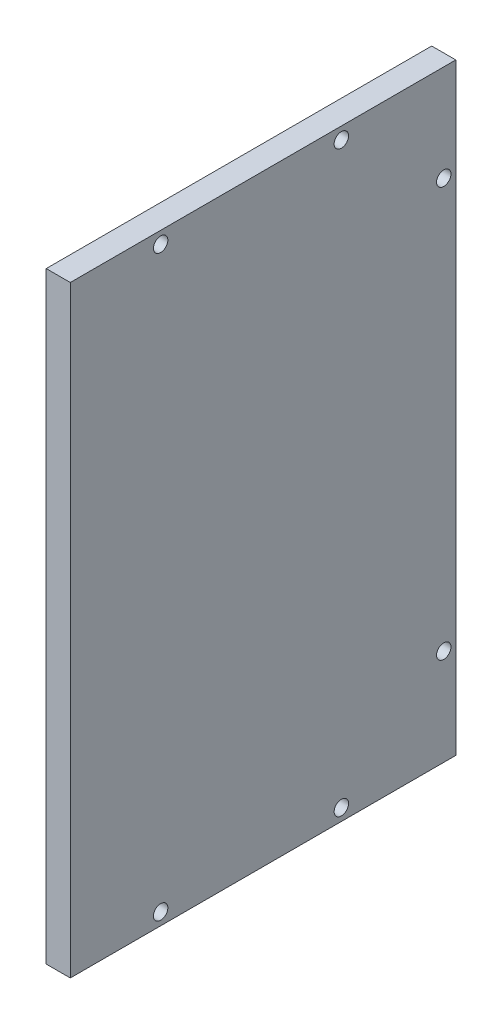
SolidWorks part; units mm, degrees
ref_plane "Front Plane" through (0, 0, 0) normal (0, 0, 1) x (1, 0, 0)
ref_plane "Top Plane" through (0, 0, 0) normal (0, 1, 0) x (1, 0, 0)
ref_plane "Right Plane" through (0, 0, 0) normal (1, 0, 0) x (0, 0, -1)
sketch "Sketch1" plane through (0, 0, 0) normal (1, 0, 0) x (0, 0, -1)
  line L1 (-50.8, -79.375) -> (50.8, -79.375)
  line L2 (-50.8, -79.375) -> (-50.8, 79.375)
  line L3 (-50.8, 79.375) -> (50.8, 79.375)
  line L4 (50.8, -79.375) -> (50.8, 79.375)
  line L5 (-50.8, -79.375) -> (50.8, 79.375) construction
  line L6 (-50.8, 79.375) -> (50.8, -79.375) construction
  point P0 (0, 0)
  dimension "D1" = 101.6
  dimension "D2" = 158.75
extrude "Boss-Extrude1" add sketch "Sketch1" along normal blind 6.35
hole_wizard "#6 Clearance Hole1" positions "Sketch2" profile "Sketch3" hole size "#6" standard "ANSI Inch" end condition through all
sketch "Sketch2" plane through (0, 0, 0) normal (-1, 0, 0) x (0, 0, 1)
  line L0 (-18.7325, -73.025) -> (-22.5425, -73.025) construction
  line L1 (-22.5425, -73.025) -> (-22.5425, -79.375) construction
  line L2 (-22.5425, -79.375) -> (-18.7325, -79.375) construction
  line L3 (-18.7325, -79.375) -> (-18.7325, -73.025) construction
  line L4 (28.8925, -73.025) -> (25.0825, -73.025) construction
  line L5 (25.0825, -73.025) -> (25.0825, -79.375) construction
  line L6 (25.0825, -79.375) -> (28.8925, -79.375) construction
  line L7 (28.8925, -79.375) -> (28.8925, -73.025) construction
  line L8 (28.8925, 79.375) -> (25.0825, 79.375) construction
  line L9 (25.0825, 79.375) -> (25.0825, 73.025) construction
  line L10 (25.0825, 73.025) -> (28.8925, 73.025) construction
  line L11 (28.8925, 73.025) -> (28.8925, 79.375) construction
  line L12 (-18.7325, 79.375) -> (-22.5425, 79.375) construction
  line L13 (-22.5425, 79.375) -> (-22.5425, 73.025) construction
  line L14 (-22.5425, 73.025) -> (-18.7325, 73.025) construction
  line L15 (-18.7325, 73.025) -> (-18.7325, 79.375) construction
  line L16 (-18.7325, -73.025) -> (-22.5425, -73.025) construction
  line L17 (-22.5425, -73.025) -> (-22.5425, -79.375) construction
  line L18 (-22.5425, -79.375) -> (-18.7325, -79.375) construction
  line L19 (-18.7325, -79.375) -> (-18.7325, -73.025) construction
  line L20 (28.8925, -73.025) -> (25.0825, -73.025) construction
  line L21 (25.0825, -73.025) -> (25.0825, -79.375) construction
  line L22 (25.0825, -79.375) -> (28.8925, -79.375) construction
  line L23 (28.8925, -79.375) -> (28.8925, -73.025) construction
  line L24 (28.8925, 79.375) -> (25.0825, 79.375) construction
  line L25 (25.0825, 79.375) -> (25.0825, 73.025) construction
  line L26 (25.0825, 73.025) -> (28.8925, 73.025) construction
  line L27 (28.8925, 73.025) -> (28.8925, 79.375) construction
  line L28 (-18.7325, 79.375) -> (-22.5425, 79.375) construction
  line L29 (-22.5425, 79.375) -> (-22.5425, 73.025) construction
  line L30 (-22.5425, 73.025) -> (-18.7325, 73.025) construction
  line L31 (-18.7325, 73.025) -> (-18.7325, 79.375) construction
  line L32 (-22.5425, 79.375) -> (-18.7325, 73.025) construction
  line L34 (25.0825, 79.375) -> (28.8925, 73.025) construction
  line L36 (-22.5425, -73.025) -> (-18.7325, -79.375) construction
  line L38 (25.0825, -73.025) -> (28.8925, -79.375) construction
  line L39 (-44.45, -55.88) -> (-44.45, -52.07) construction
  line L40 (-44.45, -52.07) -> (-50.8, -52.07) construction
  line L41 (-50.8, -52.07) -> (-50.8, -55.88) construction
  line L42 (-50.8, -55.88) -> (-44.45, -55.88) construction
  line L43 (-44.45, 52.07) -> (-44.45, 55.88) construction
  line L44 (-44.45, 55.88) -> (-50.8, 55.88) construction
  line L45 (-50.8, 55.88) -> (-50.8, 52.07) construction
  line L46 (-50.8, 52.07) -> (-44.45, 52.07) construction
  line L47 (-44.45, -55.88) -> (-44.45, -52.07) construction
  line L48 (-44.45, -52.07) -> (-50.8, -52.07) construction
  line L49 (-50.8, -52.07) -> (-50.8, -55.88) construction
  line L50 (-50.8, -55.88) -> (-44.45, -55.88) construction
  line L51 (-44.45, 52.07) -> (-44.45, 55.88) construction
  line L52 (-44.45, 55.88) -> (-50.8, 55.88) construction
  line L53 (-50.8, 55.88) -> (-50.8, 52.07) construction
  line L54 (-50.8, 52.07) -> (-44.45, 52.07) construction
  line L55 (-50.8, 55.88) -> (-44.45, 52.07) construction
  line L58 (-50.8, -52.07) -> (-44.45, -55.88) construction
  point P53 (-20.6375, 76.2)
  point P55 (26.9875, 76.2)
  point P57 (26.9875, -76.2)
  point P59 (-20.6375, -76.2)
  point P91 (-47.625, -53.975)
  point P93 (-47.625, 53.975)
sketch "Sketch3" plane through (0, 53.975, -47.625) normal (0, 1, 0) x (0, 0, 1)
  line L0 (0, 0) -> (0, 6.35)
  line L1 (0, 6.35) -> (1.8986, 6.35)
  line L2 (1.8986, 6.35) -> (1.8986, 0)
  line L5 (1.8986, 0) -> (0, 0)
  line L11 (0, -6.35) -> (0, 107.95) construction
  dimension "Thru Hole Dia." = 3.7973
  dimension "Thru Hole Depth" = 6.35
